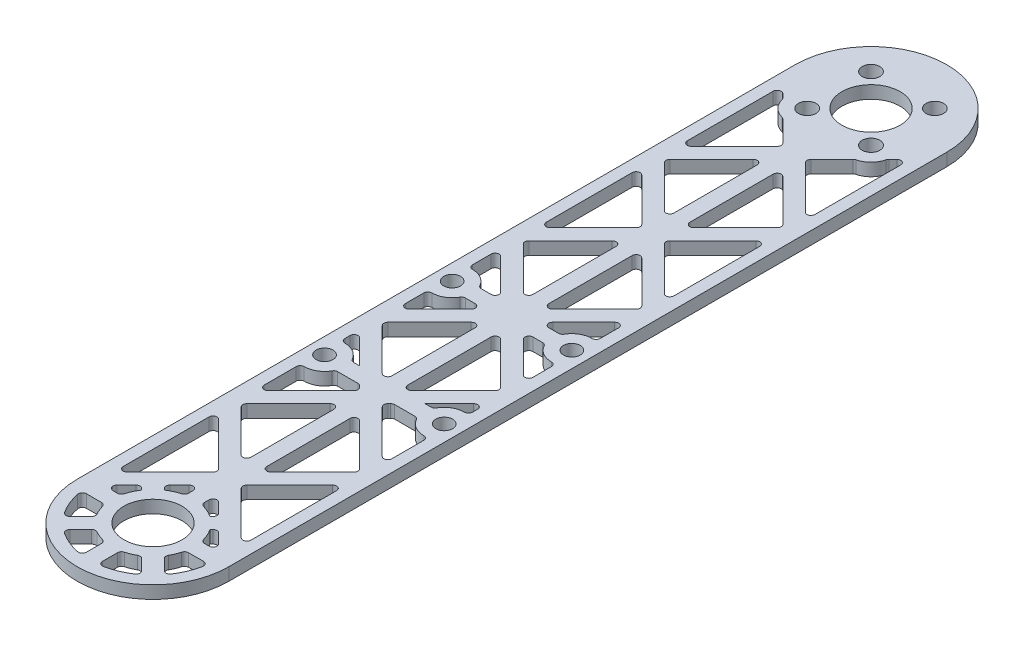
SolidWorks part; units mm, degrees
ref_plane "Front Plane" through (0, 0, 0) normal (0, 0, 1) x (1, 0, 0)
ref_plane "Top Plane" through (0, 0, 0) normal (0, 1, 0) x (1, 0, 0)
ref_plane "Right Plane" through (0, 0, 0) normal (1, 0, 0) x (0, 0, -1)
sketch "Sketch1" plane through (0, 0, 0) normal (0, 1, 0) x (1, 0, 0)
  line L0 (0, 0) -> (37733.9999, 0) construction
  line L1 (0, 0) -> (0, 37733.9999) construction
  line L2 (-19, 90) -> (-19, -90)
  line L3 (-8, 82) -> (8, 82) construction
  line L4 (-8, 82) -> (-8, 98) construction
  line L5 (-8, 98) -> (8, 98) construction
  line L6 (8, 82) -> (8, 98) construction
  line L7 (0, 98) -> (0, 82) construction
  line L8 (-8, 90) -> (8, 90) construction
  line L9 (8, -98) -> (-8, -98) construction
  line L10 (8, -98) -> (8, -82) construction
  line L11 (8, -82) -> (-8, -82) construction
  line L12 (-8, -98) -> (-8, -82) construction
  line L13 (0, -82) -> (0, -98) construction
  line L14 (8, -90) -> (-8, -90) construction
  line L15 (19, 90) -> (19, -90)
  line L16 (-19, 0) -> (-19, 50000) construction
  line L17 (19, 0) -> (19, 50000) construction
  line L18 (-15, 0) -> (-15, 50000) construction
  line L19 (23, 0) -> (23, 50000) construction
  line L20 (-23, 0) -> (-23, 50000) construction
  line L21 (15, 0) -> (15, 50000) construction
  line L22 (0, 0) -> (-35355.3391, 35355.3391) construction
  line L35 (0, 0) -> (35355.3391, 35355.3391) construction
  line L36 (-75.8437, 111.199) -> (35279.4954, -35244.14) construction
  line L37 (-52.9747, 123.6854) -> (35302.3643, -35231.6536) construction
  line L38 (-124.5684, 89.2131) -> (35230.7706, -35266.126) construction
  line L39 (-154.1581, 83.4474) -> (35201.181, -35271.8916) construction
  line L40 (-221.6173, -186.262) -> (35133.7218, 35169.0771) construction
  line L41 (-297.2701, -226.5594) -> (35058.069, 35128.7796) construction
  line L42 (-167.1815, -202.5369) -> (35188.1575, 35152.8022) construction
  line L43 (-211.8822, -282.5928) -> (35143.4569, 35072.7462) construction
  line L44 (-54.389, 122.2712) -> (35300.9501, -35233.0679) construction
  line L45 (-77.2579, 109.7848) -> (35278.0811, -35245.5542) construction
  line L46 (1.4142, 1.4142) -> (-35353.9248, 35356.7533) construction
  line L47 (-125.9826, 87.7989) -> (35229.3564, -35267.5402) construction
  line L48 (-155.5723, 82.0332) -> (35199.7667, -35273.3059) construction
  line L49 (-295.8559, -227.9736) -> (35059.4832, 35127.3654) construction
  line L50 (-220.2031, -187.6762) -> (35135.136, 35167.6629) construction
  line L51 (1.4142, -1.4142) -> (35356.7533, 35353.9248) construction
  line L52 (-165.7673, -203.9511) -> (35189.5717, 35151.388) construction
  line L53 (-210.468, -284.0071) -> (35144.8711, 35071.332) construction
  line L54 (-51.5605, 125.0996) -> (35303.7785, -35230.2394) construction
  line L55 (-74.4295, 112.6133) -> (35280.9096, -35242.7258) construction
  line L56 (-1.4142, -1.4142) -> (-35356.7533, 35353.9248) construction
  line L57 (-123.1542, 90.6273) -> (35232.1848, -35264.7118) construction
  line L58 (-152.7439, 84.8616) -> (35202.5952, -35270.4774) construction
  line L59 (-298.6843, -225.1452) -> (35056.6547, 35130.1939) construction
  line L60 (-223.0315, -184.8477) -> (35132.3075, 35170.4913) construction
  line L61 (-1.4142, 1.4142) -> (35353.9248, 35356.7533) construction
  line L62 (-168.5958, -201.1227) -> (35186.7433, 35154.2164) construction
  line L63 (-213.2964, -281.1786) -> (35142.0427, 35074.1604) construction
  line L64 (2, 0) -> (2, 37733.9999) construction
  line L65 (-2, 0) -> (-2, 37733.9999) construction
  line L66 (0, -2) -> (37733.9999, -2) construction
  line L67 (0, 2) -> (37733.9999, 2) construction
  circle A0 centre (0, 90) radius 7.3
  circle A1 centre (0, -90) radius 7.3
  circle A2 centre (0, 90) radius 16 construction
  circle A3 centre (0, -90) radius 16 construction
  circle A4 centre (-8, 98) radius 2.2
  circle A5 centre (8, 98) radius 2.2
  circle A6 centre (-8, 82) radius 2.2
  circle A7 centre (8, 82) radius 2.2
  circle A8 centre (0, 90) radius 19 construction
  circle A9 centre (0, -90) radius 19 construction
  arc A10 (-19, 90) -> (19, 90) centre (0, 90) cw
  arc A11 (-19, -90) -> (19, -90) centre (0, -90) ccw
  circle A24 centre (15, 0) radius 2.1
  circle A25 centre (15, -32) radius 2.1
  circle A26 centre (-15, 0) radius 2.1
  circle A27 centre (-15, -32) radius 2.1
  point P40 (-19, 0)
  point P43 (19, 0)
  point P146 (0, 0)
  point P147 (-13, -55.5037)
  point P148 (13, -55.5037)
  point P149 (0, 0)
  point P150 (-13, -27.9933)
  point P151 (-13, 0)
  dimension "D1" = 14.6
  dimension "D2" = 14.6
  dimension "D5" = 32
  dimension "D7" = 4.4
  dimension "35" = 38
  dimension "D8" = 4.2
  dimension "D3" = 90
  dimension "D4" = 90
  dimension "D6" = 16
  dimension "D16" = 45
  dimension "D17" = 25
  dimension "D18" = 25
  dimension "D19" = 25
  dimension "D20" = 25
  dimension "D21" = 25
  dimension "D22" = 25
  dimension "D23" = 25
  dimension "D24" = 25
  dimension "D29" = 32
  dimension "D9" = 4
  dimension "D10" = 4
  dimension "D25" = 2
  dimension "D26" = 2
  dimension "D27" = 2
  dimension "D28" = 2
  dimension "D30" = 2
  dimension "D31" = 2
extrude "Boss-Extrude2" add sketch "Sketch1" along normal blind 3.175
sketch "Sketch2" plane through (0, 3.175, 0) normal (0, 1, 0) x (1, 0, 0)
  line L8 (-19, 90) -> (-19, -90)
  line L9 (19, -90) -> (19, 90)
  line L10 (-16, 46.1127) -> (-16, 24.598)
  line L11 (-14.2929, 23.8909) -> (-3.5355, 34.6482)
  line L12 (-3.5355, 36.0624) -> (-14.2929, 46.8198)
  line L13 (-3.7071, 28.8198) -> (-14.1421, 18.3848)
  line L18 (-19, 90) -> (-19, -90) construction
  line L19 (19, -90) -> (19, 90) construction
  line L20 (-22, 90) -> (-22, -90) construction
  line L21 (22, -90) -> (22, 90) construction
  line L22 (-16, 90) -> (-16, -90) construction
  line L23 (16, -90) -> (16, 90) construction
  line L24 (0, 0) -> (0, 50000) construction
  line L25 (0, 0) -> (50000, 0) construction
  line L26 (0, 0) -> (-34966.926, 34966.926) construction
  line L27 (0, 0) -> (34966.926, 34966.926) construction
  line L28 (-61.3396, 96.695) -> (35293.9994, -35258.6441) construction
  line L29 (-52.5756, 123.2862) -> (35302.7635, -35232.0528) construction
  line L30 (-138.9176, 103.5622) -> (35216.4215, -35251.7768) construction
  line L31 (-203.3188, 132.6081) -> (35152.0202, -35222.7309) construction
  line L32 (114.4084, 149.7637) -> (-35240.9307, -35205.5754) construction
  line L33 (194.9897, 159.6343) -> (-35160.3494, -35195.7047) construction
  line L34 (352.3585, 281.6478) -> (-35002.9806, -35073.6913) construction
  line L35 (191.1578, 261.8684) -> (-35164.1813, -35093.4706) construction
  line L36 (1.4142, 1.4142) -> (-34965.5117, 34968.3402) construction
  line L37 (-62.7538, 95.2807) -> (35292.5852, -35260.0583) construction
  line L38 (-53.9898, 121.872) -> (35301.3493, -35233.467) construction
  line L39 (-140.3318, 102.148) -> (35215.0073, -35253.191) construction
  line L40 (-204.733, 131.1939) -> (35150.606, -35224.1451) construction
  line L41 (1.4142, -1.4142) -> (34968.3402, 34965.5117) construction
  line L42 (112.9942, 151.1779) -> (-35242.3449, -35204.1611) construction
  line L43 (193.5755, 161.0486) -> (-35161.7636, -35194.2905) construction
  line L44 (350.9442, 283.062) -> (-35004.3948, -35072.2771) construction
  line L45 (189.7435, 263.2827) -> (-35165.5955, -35092.0564) construction
  line L46 (-1.4142, -1.4142) -> (-34968.3402, 34965.5117) construction
  line L47 (-59.9254, 98.1092) -> (35295.4137, -35257.2299) construction
  line L48 (-51.1613, 124.7004) -> (35304.1777, -35230.6386) construction
  line L49 (-137.5034, 104.9765) -> (35217.8357, -35250.3626) construction
  line L50 (-201.9046, 134.0224) -> (35153.4344, -35221.3167) construction
  line L51 (-1.4142, 1.4142) -> (34965.5117, 34968.3402) construction
  line L52 (115.8226, 148.3495) -> (-35239.5165, -35206.9896) construction
  line L53 (196.4039, 158.2201) -> (-35158.9352, -35197.1189) construction
  line L54 (353.7727, 280.2336) -> (-35001.5664, -35075.1055) construction
  line L55 (192.572, 260.4542) -> (-35162.7671, -35094.8848) construction
  line L56 (2, 0) -> (2, 50000) construction
  line L57 (-2, 0) -> (-2, 50000) construction
  line L68 (16, -10.7574) -> (16, -6.1)
  line L69 (16, 10.7574) -> (16, 6.1)
  line L70 (2, -7.2426) -> (2, -28.1127)
  line L71 (3.7071, -28.8198) -> (14.1421, -18.3848)
  line L72 (14.1421, -16.9706) -> (3.7071, -6.5355)
  line L77 (2, -42.598) -> (2, -63.468)
  line L78 (3.7071, -64.1751) -> (14.1421, -53.7401)
  line L79 (3.7071, -41.8909) -> (14.1421, -52.3259)
  line L80 (16, -59.9533) -> (16, -81.468)
  line L81 (14.2929, -82.1751) -> (3.5355, -71.4178)
  line L82 (3.5355, -70.0036) -> (14.2929, -59.2462)
  line L83 (0, -90) -> (-35355.3391, 35265.3391) construction
  line L84 (0, -90) -> (35355.3391, 35265.3391) construction
  line L85 (1.4142, -91.4142) -> (35356.7533, 35263.9248) construction
  line L86 (1.4142, -88.5858) -> (-35353.9248, 35266.7533) construction
  line L87 (-1.4142, -88.5858) -> (35353.9248, 35266.7533) construction
  line L88 (-1.4142, -91.4142) -> (-35356.7533, 35263.9248) construction
  line L89 (2, -77.9533) -> (2, -79.1055)
  line L90 (3.7071, -77.2462) -> (6.1091, -79.6482)
  line L91 (6.1091, -81.0624) -> (5.7304, -81.4412)
  line L92 (8.9376, -83.8909) -> (8.5588, -84.2696)
  line L93 (10.3518, -83.8909) -> (12.7538, -86.2929)
  line L94 (9.1178, -96.2894) -> (11.8065, -98.9781)
  line L96 (2, -100.8945) -> (2, -104.6969)
  line L97 (6.2894, -99.1178) -> (8.9781, -101.8065)
  line L110 (-3.7071, -28.8198) -> (-14.1421, -18.3848)
  line L111 (-2, -7.2426) -> (-2, -28.1127)
  line L112 (-14.1421, -16.9706) -> (-3.7071, -6.5355)
  line L117 (-2, -42.598) -> (-2, -63.468)
  line L118 (-3.7071, -64.1751) -> (-14.1421, -53.7401)
  line L119 (-3.7071, -41.8909) -> (-14.1421, -52.3259)
  line L120 (-14.2929, -82.1751) -> (-3.5355, -71.4178)
  line L121 (-16, -59.9533) -> (-16, -81.468)
  line L122 (-3.5355, -70.0036) -> (-14.2929, -59.2462)
  line L123 (-2, -77.9533) -> (-2, -79.1055)
  line L124 (-3.7071, -77.2462) -> (-6.1091, -79.6482)
  line L125 (-6.1091, -81.0624) -> (-5.7304, -81.4412)
  line L126 (-2, -100.8945) -> (-2, -104.6969)
  line L127 (-6.2894, -99.1178) -> (-8.9781, -101.8065)
  line L132 (0, -2) -> (50000, -2) construction
  line L133 (0, 2) -> (50000, 2) construction
  line L134 (7.2426, 2) -> (9.6887, 2)
  line L135 (7.2426, -2) -> (9.6887, -2)
  line L136 (6.5355, -3.7071) -> (14.2929, -11.4645)
  line L137 (14.2929, 11.4645) -> (6.5355, 3.7071)
  line L138 (-7.2426, -2) -> (-9.6887, -2)
  line L139 (-6.5355, -3.7071) -> (-14.2929, -11.4645)
  line L140 (-16, -10.7574) -> (-16, -6.1)
  line L141 (-16, 10.7574) -> (-16, 6.1)
  line L142 (-14.2929, 11.4645) -> (-6.5355, 3.7071)
  line L143 (-7.2426, 2) -> (-9.6887, 2)
  line L167 (0, -90) -> (50000, -90) construction
  line L168 (0, -92) -> (50000, -92) construction
  line L169 (0, -88) -> (50000, -88) construction
  line L170 (10.8945, -92) -> (14.6969, -92)
  line L171 (10.8945, -88) -> (12.0467, -88)
  line L172 (-10.8945, -92) -> (-14.6969, -92)
  line L173 (-9.1178, -96.2894) -> (-11.8065, -98.9781)
  line L174 (-8.9376, -83.8909) -> (-8.5588, -84.2696)
  line L175 (-10.3518, -83.8909) -> (-12.7538, -86.2929)
  line L176 (-10.8945, -88) -> (-12.0467, -88)
  line L177 (15, -32) -> (-49985, -32) construction
  line L178 (15, -30) -> (-49985, -30) construction
  line L179 (15, -34) -> (-49985, -34) construction
  line L180 (-16, -24.598) -> (-16, -25.9)
  line L181 (-14.2929, -23.8909) -> (-8.1838, -30)
  line L182 (-8.1838, -30) -> (-9.6887, -30)
  line L183 (-9.6887, -34) -> (-4.598, -34)
  line L184 (-3.8909, -34.2929) -> (-3.5355, -34.6482)
  line L185 (-3.5355, -36.0624) -> (-14.2929, -46.8198)
  line L186 (-16, -46.1127) -> (-16, -38.1)
  line L187 (16, -24.598) -> (16, -25.9)
  line L188 (14.2929, -23.8909) -> (8.1838, -30)
  line L189 (8.1838, -30) -> (9.6887, -30)
  line L190 (16, -46.1127) -> (16, -38.1)
  line L191 (3.5355, -36.0624) -> (14.2929, -46.8198)
  line L192 (3.8909, -34.2929) -> (3.5355, -34.6482)
  line L193 (9.6887, -34) -> (4.598, -34)
  line L194 (-14.1421, 16.9706) -> (-3.7071, 6.5355)
  line L195 (-2, 7.2426) -> (-2, 28.1127)
  line L196 (-3.7071, 64.1751) -> (-14.1421, 53.7401)
  line L197 (-14.1421, 52.3259) -> (-3.7071, 41.8909)
  line L198 (-2, 42.598) -> (-2, 63.468)
  line L199 (-16, 81.468) -> (-16, 59.9533)
  line L200 (-14.2929, 59.2462) -> (-3.5355, 70.0036)
  line L201 (-3.5355, 71.4178) -> (-8.8145, 76.6967)
  line L202 (-14.2929, 82.1751) -> (-13.3033, 81.1855)
  line L203 (14.1421, 16.9706) -> (3.7071, 6.5355)
  line L204 (3.7071, 28.8198) -> (14.1421, 18.3848)
  line L205 (2, 7.2426) -> (2, 28.1127)
  line L206 (14.2929, 23.8909) -> (3.5355, 34.6482)
  line L207 (16, 46.1127) -> (16, 24.598)
  line L208 (3.5355, 36.0624) -> (14.2929, 46.8198)
  line L209 (14.1421, 52.3259) -> (3.7071, 41.8909)
  line L210 (3.7071, 64.1751) -> (14.1421, 53.7401)
  line L211 (2, 42.598) -> (2, 63.468)
  line L212 (14.2929, 82.1751) -> (13.3033, 81.1855)
  line L213 (16, 81.468) -> (16, 59.9533)
  line L214 (14.2929, 59.2462) -> (3.5355, 70.0036)
  line L215 (3.5355, 71.4178) -> (8.8145, 76.6967)
  circle A0 centre (-15, 0) radius 5.1 construction
  circle A1 centre (-15, -32) radius 5.1 construction
  circle A6 centre (15, 0) radius 5.1 construction
  circle A7 centre (0, 90) radius 7.3
  circle A8 centre (0, 90) radius 7.3 construction
  circle A9 centre (0, -90) radius 7.3
  circle A10 centre (0, -90) radius 7.3 construction
  circle A11 centre (-8, 98) radius 2.2
  circle A12 centre (-8, 98) radius 2.2 construction
  circle A13 centre (8, 98) radius 2.2
  circle A14 centre (8, 98) radius 2.2 construction
  circle A15 centre (-8, 82) radius 2.2
  circle A16 centre (-8, 82) radius 2.2 construction
  circle A17 centre (8, 82) radius 2.2
  circle A18 centre (8, 82) radius 2.2 construction
  arc A19 (19, 90) -> (-19, 90) centre (0, 90) ccw construction
  arc A21 (-13.041, 80.7238) -> (-9.2762, 76.959) centre (-8, 82) ccw
  arc A23 (13.041, 80.7238) -> (9.2762, 76.959) centre (8, 82) cw
  arc A25 (16, 59.9533) -> (14.2929, 59.2462) centre (15, 59.9533) cw
  circle A27 centre (15, 0) radius 2.1
  circle A28 centre (15, 0) radius 2.1 construction
  circle A29 centre (15, -32) radius 2.1
  circle A30 centre (15, -32) radius 2.1 construction
  circle A31 centre (-15, 0) radius 2.1
  circle A32 centre (-15, 0) radius 2.1 construction
  circle A33 centre (-15, -32) radius 2.1
  circle A34 centre (-15, -32) radius 2.1 construction
  circle A35 centre (15, -32) radius 5.1 construction
  arc A36 (19, 90) -> (-19, 90) centre (0, 90) ccw
  arc A37 (-19, -90) -> (19, -90) centre (0, -90) ccw
  arc A38 (19, 90) -> (-19, 90) centre (0, 90) ccw construction
  arc A39 (-19, -90) -> (19, -90) centre (0, -90) ccw construction
  circle A40 centre (0, -90) radius 10.3 construction
  circle A45 centre (0, 90) radius 10.3 construction
  circle A46 centre (-8, 82) radius 5.2 construction
  circle A47 centre (8, 82) radius 5.2 construction
  circle A48 centre (8, 98) radius 5.2 construction
  circle A49 centre (-8, 98) radius 5.2 construction
  arc A50 (22, 90) -> (-22, 90) centre (0, 90) ccw construction
  arc A51 (-22, -90) -> (22, -90) centre (0, -90) ccw construction
  arc A52 (16, 90) -> (-16, 90) centre (0, 90) ccw construction
  arc A53 (-16, -90) -> (16, -90) centre (0, -90) ccw construction
  arc A54 (-16, 90) -> (16, 90) centre (0, 90) ccw construction
  arc A62 (2.7345, -80.0696) -> (5.7304, -81.4412) centre (0, -90) cw
  arc A63 (2.7345, -99.9304) -> (5.0882, -98.9554) centre (0, -90) ccw
  arc A64 (3.2, -105.6767) -> (8.8224, -103.3479) centre (0, -90) ccw
  arc A70 (-2.7345, -80.0696) -> (-5.7304, -81.4412) centre (0, -90) ccw
  arc A71 (-2.7345, -99.9304) -> (-5.0882, -98.9554) centre (0, -90) cw
  arc A72 (-3.2, -105.6767) -> (-8.8224, -103.3479) centre (0, -90) cw
  arc A75 (15, 5.1) -> (10.5594, 2.5082) centre (15, 0) ccw
  arc A76 (10.5594, -2.5082) -> (15, -5.1) centre (15, 0) ccw
  arc A77 (-10.5594, -2.5082) -> (-15, -5.1) centre (-15, 0) cw
  arc A78 (-15, 5.1) -> (-10.5594, 2.5082) centre (-15, 0) cw
  arc A81 (8.5588, -84.2696) -> (9.9304, -87.2655) centre (0, -90) cw
  arc A82 (8.9554, -95.0882) -> (9.9304, -92.7345) centre (0, -90) ccw
  arc A83 (15.6767, -93.2) -> (13.3479, -98.8224) centre (0, -90) cw
  arc A84 (-8.9554, -95.0882) -> (-9.9304, -92.7345) centre (0, -90) cw
  arc A85 (-15.6767, -93.2) -> (-13.3479, -98.8224) centre (0, -90) ccw
  arc A86 (-8.5588, -84.2696) -> (-9.9304, -87.2655) centre (0, -90) ccw
  arc A87 (-15, -26.9) -> (-10.5594, -29.4918) centre (-15, -32) cw
  arc A88 (-15, -37.1) -> (-10.5594, -34.5082) centre (-15, -32) ccw
  arc A89 (15, -26.9) -> (10.5594, -29.4918) centre (15, -32) ccw
  arc A90 (15, -37.1) -> (10.5594, -34.5082) centre (15, -32) cw
  arc A91 (16, -59.9533) -> (14.2929, -59.2462) centre (15, -59.9533) ccw
  arc A92 (3.5355, -71.4178) -> (3.5355, -70.0036) centre (4.2426, -70.7107) cw
  arc A93 (12.7538, -86.2929) -> (12.0467, -88) centre (12.0467, -87) cw
  arc A94 (9.9304, -87.2655) -> (10.8945, -88) centre (10.8945, -87) ccw
  arc A95 (8.9376, -83.8909) -> (10.3518, -83.8909) centre (9.6447, -84.598) cw
  arc A96 (-6.1091, -79.6482) -> (-6.1091, -81.0624) centre (-5.402, -80.3553) ccw
  arc A97 (-2, -79.1055) -> (-2.7345, -80.0696) centre (-3, -79.1055) cw
  arc A98 (-2, -77.9533) -> (-3.7071, -77.2462) centre (-3, -77.9533) ccw
  arc A99 (2, -77.9533) -> (3.7071, -77.2462) centre (3, -77.9533) cw
  arc A100 (2, -79.1055) -> (2.7345, -80.0696) centre (3, -79.1055) ccw
  arc A101 (6.1091, -79.6482) -> (6.1091, -81.0624) centre (5.402, -80.3553) cw
  arc A102 (16, -81.468) -> (14.2929, -82.1751) centre (15, -81.468) cw
  arc A103 (14.6969, -92) -> (15.6767, -93.2) centre (14.6969, -93) cw
  arc A104 (11.8065, -98.9781) -> (13.3479, -98.8224) centre (12.5136, -98.271) ccw
  arc A105 (9.9304, -92.7345) -> (10.8945, -92) centre (10.8945, -93) cw
  arc A106 (9.1178, -96.2894) -> (8.9554, -95.0882) centre (9.8249, -95.5823) cw
  arc A107 (5.0882, -98.9554) -> (6.2894, -99.1178) centre (5.5823, -99.8249) cw
  arc A108 (8.8224, -103.3479) -> (8.9781, -101.8065) centre (8.271, -102.5136) ccw
  arc A109 (3.2, -105.6767) -> (2, -104.6969) centre (3, -104.6969) cw
  arc A110 (2.7345, -99.9304) -> (2, -100.8945) centre (3, -100.8945) ccw
  arc A111 (-2, -104.6969) -> (-3.2, -105.6767) centre (-3, -104.6969) cw
  arc A112 (-8.8224, -103.3479) -> (-8.9781, -101.8065) centre (-8.271, -102.5136) cw
  arc A113 (-2.7345, -99.9304) -> (-2, -100.8945) centre (-3, -100.8945) cw
  arc A114 (-5.0882, -98.9554) -> (-6.2894, -99.1178) centre (-5.5823, -99.8249) ccw
  arc A115 (-11.8065, -98.9781) -> (-13.3479, -98.8224) centre (-12.5136, -98.271) cw
  arc A116 (-8.9554, -95.0882) -> (-9.1178, -96.2894) centre (-9.8249, -95.5823) cw
  arc A117 (-10.8945, -92) -> (-9.9304, -92.7345) centre (-10.8945, -93) cw
  arc A118 (-14.6969, -92) -> (-15.6767, -93.2) centre (-14.6969, -93) ccw
  arc A119 (-9.9304, -87.2655) -> (-10.8945, -88) centre (-10.8945, -87) cw
  arc A120 (-8.9376, -83.8909) -> (-10.3518, -83.8909) centre (-9.6447, -84.598) ccw
  arc A121 (-12.7538, -86.2929) -> (-12.0467, -88) centre (-12.0467, -87) ccw
  arc A122 (-14.2929, -82.1751) -> (-16, -81.468) centre (-15, -81.468) cw
  arc A123 (-3.5355, -71.4178) -> (-3.5355, -70.0036) centre (-4.2426, -70.7107) ccw
  arc A124 (-16, -59.9533) -> (-14.2929, -59.2462) centre (-15, -59.9533) cw
  arc A125 (-14.1421, -53.7401) -> (-14.1421, -52.3259) centre (-13.435, -53.033) cw
  arc A126 (-2, -63.468) -> (-3.7071, -64.1751) centre (-3, -63.468) cw
  arc A127 (2, -63.468) -> (3.7071, -64.1751) centre (3, -63.468) ccw
  arc A128 (14.1421, -53.7401) -> (14.1421, -52.3259) centre (13.435, -53.033) ccw
  arc A129 (2, -42.598) -> (3.7071, -41.8909) centre (3, -42.598) cw
  arc A130 (16, -46.1127) -> (14.2929, -46.8198) centre (15, -46.1127) cw
  arc A131 (-3.5355, -34.6482) -> (-3.5355, -36.0624) centre (-4.2426, -35.3553) cw
  arc A132 (-4.598, -34) -> (-3.8909, -34.2929) centre (-4.598, -35) cw
  arc A133 (-9.6887, -34) -> (-10.5594, -34.5082) centre (-9.6887, -35) ccw
  arc A134 (-16, -38.1) -> (-15, -37.1) centre (-15, -38.1) cw
  arc A135 (-14.2929, -46.8198) -> (-16, -46.1127) centre (-15, -46.1127) cw
  arc A136 (-2, -42.598) -> (-3.7071, -41.8909) centre (-3, -42.598) ccw
  arc A137 (16, -38.1) -> (15, -37.1) centre (15, -38.1) ccw
  arc A138 (9.6887, -34) -> (10.5594, -34.5082) centre (9.6887, -35) cw
  arc A139 (3.8909, -34.2929) -> (4.598, -34) centre (4.598, -35) cw
  arc A140 (3.5355, -36.0624) -> (3.5355, -34.6482) centre (4.2426, -35.3553) cw
  arc A141 (9.6887, -30) -> (10.5594, -29.4918) centre (9.6887, -29) ccw
  arc A142 (16, -25.9) -> (15, -26.9) centre (15, -25.9) cw
  arc A143 (16, -24.598) -> (14.2929, -23.8909) centre (15, -24.598) ccw
  arc A144 (-16, -24.598) -> (-14.2929, -23.8909) centre (-15, -24.598) cw
  arc A145 (-16, -25.9) -> (-15, -26.9) centre (-15, -25.9) ccw
  arc A146 (-9.6887, -30) -> (-10.5594, -29.4918) centre (-9.6887, -29) cw
  arc A147 (2, -7.2426) -> (3.7071, -6.5355) centre (3, -7.2426) cw
  arc A148 (14.1421, -18.3848) -> (14.1421, -16.9706) centre (13.435, -17.6777) ccw
  arc A149 (2, -28.1127) -> (3.7071, -28.8198) centre (3, -28.1127) ccw
  arc A150 (-2, -7.2426) -> (-3.7071, -6.5355) centre (-3, -7.2426) ccw
  arc A151 (-14.1421, -18.3848) -> (-14.1421, -16.9706) centre (-13.435, -17.6777) cw
  arc A152 (-3.7071, -28.8198) -> (-2, -28.1127) centre (-3, -28.1127) ccw
  arc A153 (14.2929, -11.4645) -> (16, -10.7574) centre (15, -10.7574) ccw
  arc A154 (16, -6.1) -> (15, -5.1) centre (15, -6.1) ccw
  arc A155 (9.6887, -2) -> (10.5594, -2.5082) centre (9.6887, -3) cw
  arc A156 (7.2426, -2) -> (6.5355, -3.7071) centre (7.2426, -3) ccw
  arc A157 (-14.2929, -11.4645) -> (-16, -10.7574) centre (-15, -10.7574) cw
  arc A158 (-7.2426, -2) -> (-6.5355, -3.7071) centre (-7.2426, -3) cw
  arc A159 (-9.6887, -2) -> (-10.5594, -2.5082) centre (-9.6887, -3) ccw
  arc A160 (-16, -6.1) -> (-15, -5.1) centre (-15, -6.1) cw
  arc A161 (14.2929, 11.4645) -> (16, 10.7574) centre (15, 10.7574) cw
  arc A162 (16, 6.1) -> (15, 5.1) centre (15, 6.1) cw
  arc A163 (9.6887, 2) -> (10.5594, 2.5082) centre (9.6887, 3) ccw
  arc A164 (7.2426, 2) -> (6.5355, 3.7071) centre (7.2426, 3) cw
  arc A165 (-6.5355, 3.7071) -> (-7.2426, 2) centre (-7.2426, 3) cw
  arc A166 (-9.6887, 2) -> (-10.5594, 2.5082) centre (-9.6887, 3) cw
  arc A167 (-16, 6.1) -> (-15, 5.1) centre (-15, 6.1) ccw
  arc A168 (-16, 10.7574) -> (-14.2929, 11.4645) centre (-15, 10.7574) cw
  arc A170 (-13.3033, 81.1855) -> (-13.041, 80.7238) centre (-14.0104, 80.4784) cw
  arc A171 (-8.8145, 76.6967) -> (-9.2762, 76.959) centre (-9.5216, 75.9896) ccw
  arc A172 (13.3033, 81.1855) -> (13.041, 80.7238) centre (14.0104, 80.4784) ccw
  arc A173 (8.8145, 76.6967) -> (9.2762, 76.959) centre (9.5216, 75.9896) cw
  arc A174 (14.2929, 82.1751) -> (16, 81.468) centre (15, 81.468) cw
  arc A175 (3.5355, 70.0036) -> (3.5355, 71.4178) centre (4.2426, 70.7107) cw
  arc A176 (14.2929, 23.8909) -> (16, 24.598) centre (15, 24.598) ccw
  arc A177 (16, 46.1127) -> (14.2929, 46.8198) centre (15, 46.1127) ccw
  arc A178 (3.5355, 34.6482) -> (3.5355, 36.0624) centre (4.2426, 35.3553) cw
  arc A179 (14.1421, 16.9706) -> (14.1421, 18.3848) centre (13.435, 17.6777) ccw
  arc A180 (3.7071, 6.5355) -> (2, 7.2426) centre (3, 7.2426) cw
  arc A181 (3.7071, 28.8198) -> (2, 28.1127) centre (3, 28.1127) ccw
  arc A182 (-3.7071, 6.5355) -> (-2, 7.2426) centre (-3, 7.2426) ccw
  arc A183 (-14.1421, 18.3848) -> (-14.1421, 16.9706) centre (-13.435, 17.6777) ccw
  arc A184 (-3.7071, 28.8198) -> (-2, 28.1127) centre (-3, 28.1127) cw
  arc A185 (3.7071, 41.8909) -> (2, 42.598) centre (3, 42.598) cw
  arc A186 (14.1421, 52.3259) -> (14.1421, 53.7401) centre (13.435, 53.033) ccw
  arc A187 (3.7071, 64.1751) -> (2, 63.468) centre (3, 63.468) ccw
  arc A188 (-3.5355, 34.6482) -> (-3.5355, 36.0624) centre (-4.2426, 35.3553) ccw
  arc A189 (-16, 24.598) -> (-14.2929, 23.8909) centre (-15, 24.598) ccw
  arc A190 (-16, 46.1127) -> (-14.2929, 46.8198) centre (-15, 46.1127) cw
  arc A191 (-3.7071, 41.8909) -> (-2, 42.598) centre (-3, 42.598) ccw
  arc A192 (-3.7071, 64.1751) -> (-2, 63.468) centre (-3, 63.468) cw
  arc A193 (-14.1421, 53.7401) -> (-14.1421, 52.3259) centre (-13.435, 53.033) ccw
  arc A194 (-16, 59.9533) -> (-14.2929, 59.2462) centre (-15, 59.9533) ccw
  arc A195 (-3.5355, 70.0036) -> (-3.5355, 71.4178) centre (-4.2426, 70.7107) ccw
  arc A196 (-16, 81.468) -> (-14.2929, 82.1751) centre (-15, 81.468) cw
  point P168 (16, 57.5391)
  point P171 (-13.0993, 80.9815)
  point P174 (-9.0185, 76.9007)
  point P177 (13.0993, 80.9815)
  point P231 (9.0185, 76.9007)
  point P235 (16, 83.8823)
  point P238 (2.8284, 70.7107)
  point P241 (16, 22.1838)
  point P287 (16, 48.5269)
  point P290 (2.8284, 35.3553)
  point P293 (14.8492, 17.6777)
  point P296 (2, 4.8284)
  point P299 (2, 30.5269)
  point P331 (16, -57.5391)
  point P334 (2.8284, -70.7107)
  point P337 (14.4609, -88)
  point P340 (10.104, -88)
  point P343 (9.6447, -83.1838)
  point P346 (-6.8162, -80.3553)
  point P349 (-2, -79.896)
  point P352 (-2, -75.5391)
  point P355 (2, -75.5391)
  point P358 (2, -79.896)
  point P361 (6.8162, -80.3553)
  point P364 (16, -83.8823)
  point P367 (15.8745, -92)
  point P370 (12.6392, -99.8108)
  point P373 (10.104, -92)
  point P376 (8.5588, -95.7304)
  point P379 (5.7304, -98.5588)
  point P382 (9.8108, -102.6392)
  point P385 (2, -105.8745)
  point P388 (2, -100.104)
  point P391 (-2, -105.8745)
  point P394 (-9.8108, -102.6392)
  point P397 (-2, -100.104)
  point P400 (-5.7304, -98.5588)
  point P403 (-12.6392, -99.8108)
  point P406 (-8.5588, -95.7304)
  point P409 (-10.104, -92)
  point P412 (-15.8745, -92)
  point P415 (-10.104, -88)
  point P418 (-9.6447, -83.1838)
  point P421 (-14.4609, -88)
  point P424 (-16, -83.8823)
  point P427 (-2.8284, -70.7107)
  point P430 (-16, -57.5391)
  point P433 (-14.8492, -53.033)
  point P436 (-2, -65.8823)
  point P439 (2, -65.8823)
  point P442 (14.8492, -53.033)
  point P445 (2, -40.1838)
  point P448 (16, -48.5269)
  point P451 (-2.8284, -35.3553)
  point P454 (-4.1838, -34)
  point P457 (-10.3085, -34)
  point P460 (-16, -37.001)
  point P463 (-16, -48.5269)
  point P466 (-2, -40.1838)
  point P469 (16, -37.001)
  point P472 (10.3085, -34)
  point P475 (4.1838, -34)
  point P478 (2.8284, -35.3553)
  point P481 (10.3085, -30)
  point P484 (16, -26.999)
  point P487 (16, -22.1838)
  point P490 (-16, -22.1838)
  point P493 (-16, -26.999)
  point P496 (-10.3085, -30)
  point P499 (2, -4.8284)
  point P502 (14.8492, -17.6777)
  point P505 (2, -30.5269)
  point P508 (-2, -4.8284)
  point P511 (-14.8492, -17.6777)
  point P514 (-2, -30.5269)
  point P517 (16, -13.1716)
  point P520 (16, -5.001)
  point P523 (10.3085, -2)
  point P526 (4.8284, -2)
  point P529 (-16, -13.1716)
  point P532 (-4.8284, -2)
  point P535 (-10.3085, -2)
  point P538 (-16, -5.001)
  point P541 (16, 13.1716)
  point P544 (16, 5.001)
  point P547 (10.3085, 2)
  point P550 (4.8284, 2)
  point P553 (-4.8284, 2)
  point P556 (-10.3085, 2)
  point P559 (-16, 5.001)
  point P562 (-16, 13.1716)
  point P563 (-2, 4.8284)
  point P565 (-14.8492, 17.6777)
  point P567 (-14.8492, 17.6777)
  point P570 (-2, 30.5269)
  point P573 (2, 40.1838)
  point P574 (-2, 4.8284)
  point P577 (2, 4.8284)
  point P578 (14.8492, 53.033)
  point P581 (2, 65.8823)
  point P584 (-2.8284, 35.3553)
  point P587 (-16, 22.1838)
  point P589 (14.8492, 17.6777)
  point P591 (-16, 48.5269)
  point P594 (-2, 40.1838)
  point P595 (16, 22.1838)
  point P598 (16, 48.5269)
  point P599 (-2, 65.8823)
  point P602 (-14.8492, 53.033)
  point P605 (-16, 57.5391)
  point P607 (-16, 22.1838)
  point P609 (-2.8284, 70.7107)
  point P612 (-16, 83.8823)
  point P613 (-16, 48.5269)
  point P616 (-14.8492, 53.033)
  point P619 (14.8492, 53.033)
  point P622 (13.0993, 80.9815)
  point P625 (9.0185, 76.9007)
  point P640 (16, 57.5391)
  point P643 (-16, 57.5391)
  point P655 (-13.0993, 80.9815)
  point P658 (-9.0185, 76.9007)
  point P664 (16, 83.8823)
  point P667 (-16, 83.8823)
  dimension "D21" = 25
  dimension "D22" = 25
  dimension "D23" = 25
  dimension "D24" = 25
  dimension "D30" = 2
  dimension "D31" = 2
  dimension "D41" = 1
  dimension "D42" = 1
  dimension "D43" = 1
  dimension "D44" = 1
  dimension "D45" = 1
  dimension "D46" = 1
  dimension "D47" = 1
  dimension "D48" = 1
  dimension "D49" = 1
  dimension "D50" = 1
  dimension "D51" = 1
  dimension "D52" = 1
  dimension "D53" = 1
  dimension "D54" = 1
  dimension "D55" = 1
  dimension "D56" = 1
  dimension "D57" = 1
  dimension "D58" = 1
  dimension "D59" = 1
  dimension "D60" = 1
  dimension "D61" = 1
  dimension "D62" = 1
  dimension "D63" = 1
  dimension "D64" = 1
  dimension "D65" = 1
  dimension "D66" = 1
  dimension "D67" = 1
  dimension "D68" = 1
  dimension "D69" = 1
  dimension "D70" = 1
  dimension "D71" = 1
  dimension "D72" = 1
  dimension "D73" = 1
  dimension "D74" = 1
  dimension "D75" = 1
  dimension "D76" = 1
  dimension "D77" = 1
  dimension "D78" = 1
  dimension "D79" = 1
  dimension "D80" = 1
  dimension "D81" = 1
  dimension "D82" = 1
  dimension "D83" = 1
  dimension "D84" = 1
  dimension "D85" = 1
  dimension "D86" = 1
  dimension "D87" = 1
  dimension "D88" = 1
  dimension "D89" = 1
  dimension "D90" = 1
  dimension "D91" = 1
  dimension "D92" = 1
  dimension "D93" = 1
  dimension "D94" = 1
  dimension "D95" = 1
  dimension "D96" = 1
  dimension "D97" = 1
  dimension "D98" = 1
  dimension "D99" = 1
  dimension "D100" = 1
  dimension "D101" = 1
  dimension "D102" = 1
  dimension "D103" = 1
  dimension "D104" = 1
  dimension "D105" = 1
  dimension "D106" = 1
  dimension "D107" = 1
  dimension "D108" = 1
  dimension "D109" = 1
  dimension "D110" = 1
  dimension "D111" = 1
  dimension "D112" = 1
  dimension "D113" = 1
  dimension "D114" = 1
  dimension "D115" = 1
  dimension "D116" = 1
  dimension "D117" = 1
  dimension "D118" = 1
  dimension "D119" = 1
  dimension "D120" = 1
  dimension "D121" = 1
  dimension "D122" = 1
  dimension "D123" = 1
  dimension "D124" = 1
  dimension "D125" = 1
  dimension "D126" = 1
  dimension "D127" = 1
  dimension "D128" = 1
  dimension "D129" = 1
  dimension "D130" = 1
  dimension "D131" = 1
  dimension "D132" = 1
  dimension "D133" = 1
  dimension "D134" = 1
  dimension "D135" = 1
  dimension "D136" = 1
  dimension "D137" = 1
  dimension "D138" = 1
  dimension "D139" = 1
  dimension "D140" = 1
  dimension "D141" = 1
  dimension "D142" = 1
  dimension "D143" = 1
  dimension "D144" = 1
  dimension "D145" = 1
  dimension "D146" = 1
  dimension "D20" = 45
  dimension "D25" = 25
  dimension "D26" = 25
  dimension "D27" = 25
  dimension "D28" = 25
  dimension "D1" = 0
  dimension "D2" = 0
  dimension "D3" = 0
  dimension "D4" = 0
  dimension "D5" = 0
  dimension "D6" = 0
  dimension "D12" = 0
  dimension "D13" = 0
  dimension "D14" = 0
  dimension "D15" = 0
  dimension "D16" = 0
  dimension "D17" = 3
  dimension "D18" = 3
  dimension "D19" = 3
  dimension "D29" = 2
  dimension "D32" = 2
  dimension "D33" = 2
  dimension "D34" = 2
  dimension "D35" = 2
  dimension "D36" = 2
  dimension "D37" = 2
  dimension "D38" = 2
  dimension "D39" = 2
  dimension "D40" = 2
extrude "Cut-Extrude1" cut sketch "Sketch2" against normal blind 3.175
equation "\"pocketing\" = \"strut pocketing\" * 2"
equation "\"strut pocketing\" = 2mm"
equation "\"D10@Sketch1\"=\"pocketing\""
equation "\"D9@Sketch1\"=\"pocketing\""
equation "\"dist struts\"= 25mm"
equation "\"D17@Sketch1\"=\"dist struts\""
equation "\"D18@Sketch1\"=\"dist struts\""
equation "\"D20@Sketch1\"=\"dist struts\""
equation "\"D19@Sketch1\"=\"dist struts\""
equation "\"D21@Sketch1\"=\"dist struts\""
equation "\"D22@Sketch1\"=\"dist struts\""
equation "\"D23@Sketch1\"=\"dist struts\""
equation "\"D24@Sketch1\"=\"dist struts\""
equation "\"D25@Sketch1\"=\"strut pocketing\""
equation "\"D26@Sketch1\"=\"strut pocketing\""
equation "\"D28@Sketch1\"=\"strut pocketing\""
equation "\"D27@Sketch1\"=\"strut pocketing\""
equation "\"D21@Sketch2\"=\"dist struts\""
equation "\"D22@Sketch2\"=\"dist struts\""
equation "\"D23@Sketch2\"=\"dist struts\""
equation "\"D24@Sketch2\"=\"dist struts\""
equation "\"D25@Sketch2\"=\"dist struts\""
equation "\"D26@Sketch2\"=\"dist struts\""
equation "\"D27@Sketch2\"=\"dist struts\""
equation "\"D28@Sketch2\"=\"dist struts\""
equation "\"D31@Sketch2\"=\"strut pocketing\""
equation "\"D32@Sketch2\"=\"strut pocketing\""
equation "\"D29@Sketch2\"=\"strut pocketing\""
equation "\"D30@Sketch2\"=\"strut pocketing\""
equation "\"D34@Sketch2\"=\"strut pocketing\""
equation "\"D33@Sketch2\"=\"strut pocketing\""
equation "\"D31@Sketch1\"=\"strut pocketing\""
equation "\"D30@Sketch1\"=\"strut pocketing\""
equation "\"D36@Sketch2\"=\"strut pocketing\""
equation "\"D35@Sketch2\"=\"strut pocketing\""
equation "\"D38@Sketch2\"=\"strut pocketing\""
equation "\"D37@Sketch2\"=\"strut pocketing\""
equation "\"D39@Sketch2\"=\"strut pocketing\""
equation "\"D40@Sketch2\"=\"strut pocketing\""
